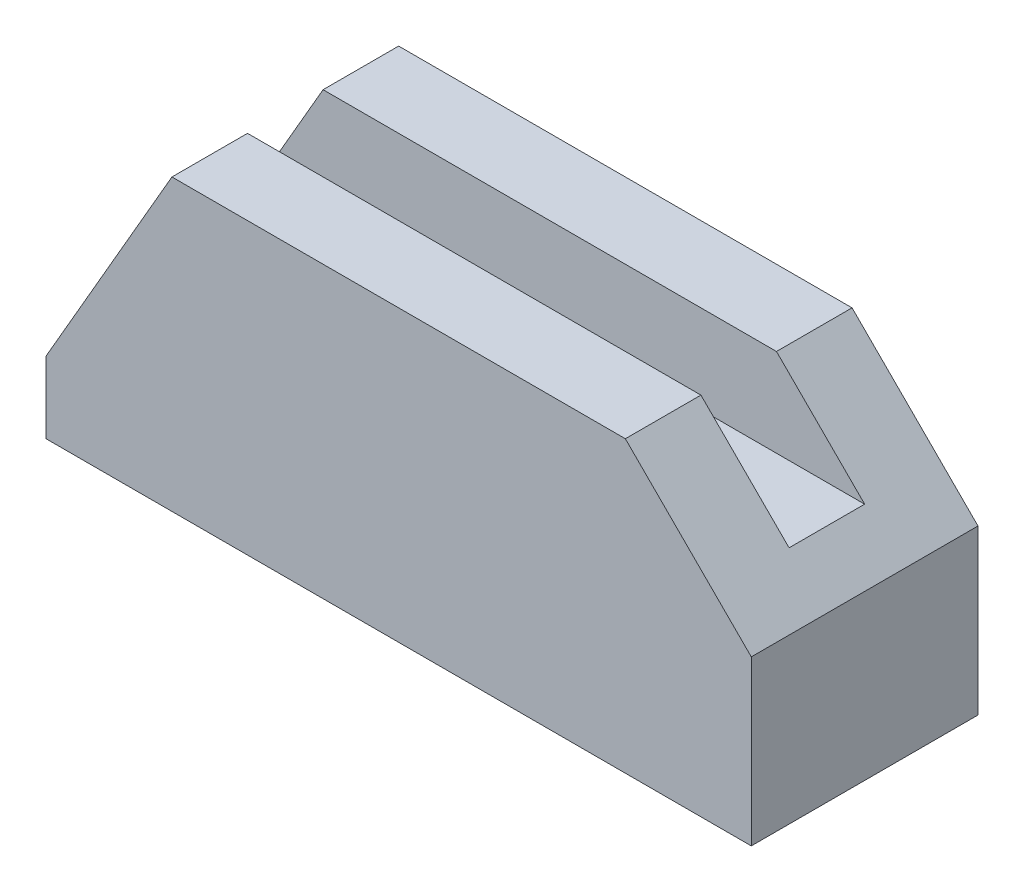
SolidWorks part; units mm, degrees
material "Thornel Mat VMA"
ref_plane "Front Plane" through (0, 0, 0) normal (0, 0, 1) x (1, 0, 0)
ref_plane "Top Plane" through (0, 0, 0) normal (0, 1, 0) x (1, 0, 0)
ref_plane "Right Plane" through (0, 0, 0) normal (1, 0, 0) x (0, 0, -1)
sketch "Sketch1" plane through (0, 0, 0) normal (0, 0, 1) x (1, 0, 0)
  line L0 (-28, 0) -> (28, 0)
  line L1 (28, 0) -> (28, 13)
  line L2 (28, 13) -> (18, 23)
  line L3 (18, 23) -> (-18, 23)
  line L4 (-18, 23) -> (-28, 5.6795)
  line L5 (-28, 5.6795) -> (-28, 0)
  point P3 (-28, 16.8792)
  point P8 (0, 0)
  point P9 (0, 23)
  dimension "D1" = 135
  dimension "D2" = 150
  dimension "D3" = 56
  dimension "D4" = 36
  dimension "D5" = 13
extrude "Boss-Extrude1" add sketch "Sketch1" along normal mid plane 18
sketch "Sketch2" plane through (0, 23, 0) normal (0, 1, 0) x (1, 0, 0)
  line L1 (-103.3794, 3) -> (103.3794, 3)
  line L2 (-103.3794, 3) -> (-103.3794, -3)
  line L3 (-103.3794, -3) -> (103.3794, -3)
  line L4 (103.3794, 3) -> (103.3794, -3)
  line L5 (-103.3794, 3) -> (103.3794, -3) construction
  line L6 (-103.3794, -3) -> (103.3794, 3) construction
  point P0 (0, 0)
  dimension "D1" = 6
extrude "Cut-Extrude1" cut sketch "Sketch2" against normal blind 7
